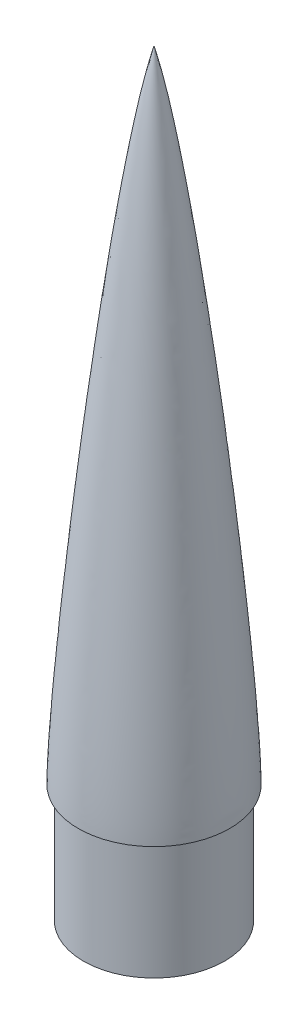
SolidWorks part; units mm, degrees
ref_plane "Front Plane" through (0, 0, 0) normal (0, 0, 1) x (1, 0, 0)
ref_plane "Top Plane" through (0, 0, 0) normal (0, 1, 0) x (1, 0, 0)
ref_plane "Right Plane" through (0, 0, 0) normal (1, 0, 0) x (0, 0, -1)
sketch "Sketch2" plane through (0, 0, 0) normal (0, 0, 1) x (1, 0, 0)
  line L0 (0, 0) -> (0, 334.8164) construction
  line L1 (0, 0) -> (-5.5, 0)
  line L2 (-5.5, 0) -> (-5.5, 7)
  line L3 (-5.5, 7) -> (-27, 12)
  line L4 (-27, 12) -> (-27, 57)
  line L5 (-27, 57) -> (-29, 57)
  line L6 (-29, 57) -> (-29, 126.2814) construction
  line L7 (0, 0) -> (0, 302)
  spline S0 degree 3 poles (-29, 57) (-28.8218, 95.9593) (-11.9525, 259.849) (0, 302) knots 0 0 0 0 0.899177 0.899177 0.899177 0.899177
  point P3 (0, 0)
  point P11 (0, 334.8164)
  dimension "D8" = 131.4387
  dimension "D1" = 5.5
  dimension "D2" = 27
  dimension "D3" = 2
  dimension "D4" = 12
  dimension "D5" = 7
  dimension "D6" = 45
  dimension "D7" = 245
revolve "Revolve1" add sketch "Sketch2" angle 360 about L7
